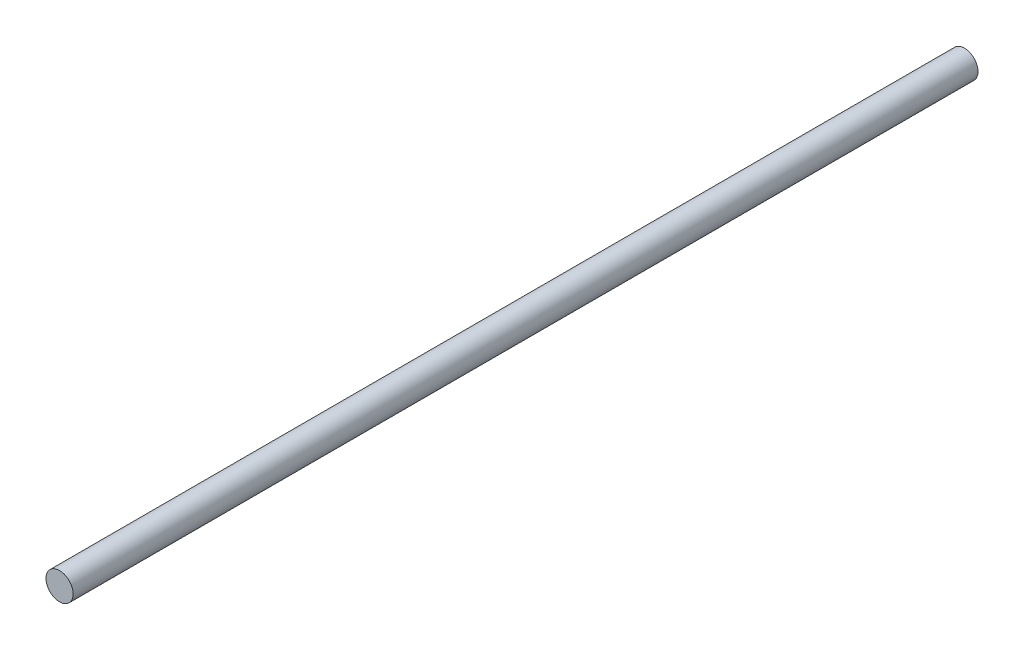
SolidWorks part; units mm, degrees
material "AISI 1020"
ref_plane "Front Plane" through (0, 0, 0) normal (0, 0, 1) x (1, 0, 0)
ref_plane "Top Plane" through (0, 0, 0) normal (0, 1, 0) x (1, 0, 0)
ref_plane "Right Plane" through (0, 0, 0) normal (1, 0, 0) x (0, 0, -1)
sketch "Sketch1" plane through (0, 0, 0) normal (0, 0, 1) x (1, 0, 0)
  circle A0 centre (0, 0) radius 6
  dimension "D1" = 12
extrude "Boss-Extrude1" add sketch "Sketch1" along normal mid plane 400
